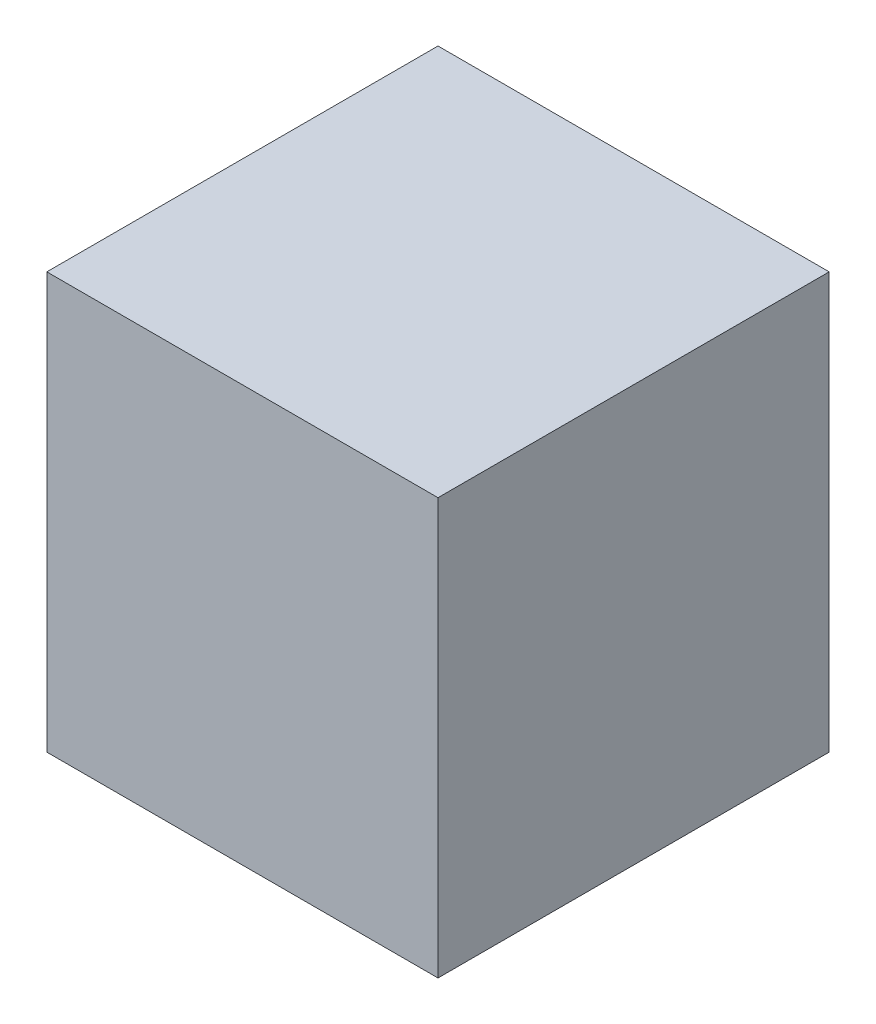
SolidWorks part; units mm, degrees
ref_plane "Front Plane" through (0, 0, 0) normal (0, 0, 1) x (1, 0, 0)
ref_plane "Top Plane" through (0, 0, 0) normal (0, 1, 0) x (1, 0, 0)
ref_plane "Right Plane" through (0, 0, 0) normal (1, 0, 0) x (0, 0, -1)
sketch "Sketch1" plane through (0, 0, 0) normal (0, 0, 1) x (1, 0, 0)
  line L1 (-28.4, -30.2) -> (28.4, -30.2)
  line L2 (-28.4, -30.2) -> (-28.4, 30.2)
  line L3 (-28.4, 30.2) -> (28.4, 30.2)
  line L4 (28.4, -30.2) -> (28.4, 30.2)
  line L5 (-28.4, -30.2) -> (28.4, 30.2) construction
  line L6 (-28.4, 30.2) -> (28.4, -30.2) construction
  point P0 (0, 0)
extrude "Envelope" add sketch "Sketch1" along normal blind 56.8
